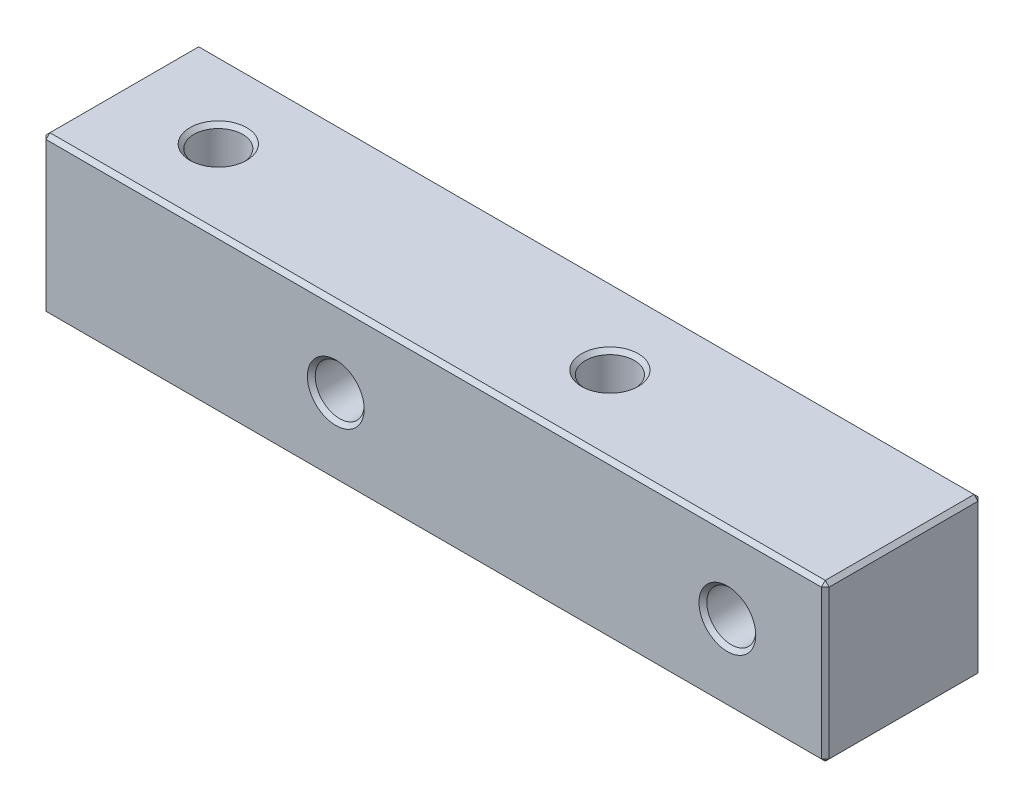
SolidWorks part; units mm, degrees
ref_plane "前视基准面" through (0, 0, 0) normal (0, 0, 1) x (1, 0, 0)
ref_plane "上视基准面" through (0, 0, 0) normal (0, 1, 0) x (1, 0, 0)
ref_plane "右视基准面" through (0, 0, 0) normal (1, 0, 0) x (0, 0, -1)
sketch "草图1" plane through (0, 0, 0) normal (0, 1, 0) x (1, 0, 0)
  line L1 (-20, 4) -> (20, 4)
  line L2 (-20, 4) -> (-20, -4)
  line L3 (-20, -4) -> (20, -4)
  line L4 (20, 4) -> (20, -4)
  line L5 (-20, 4) -> (20, -4) construction
  line L6 (-20, -4) -> (20, 4) construction
  point P0 (0, 0)
  dimension "D1" = 8
  dimension "D2" = 40
extrude "凸台-拉伸1" add sketch "草图1" along normal mid plane 8
hole_wizard "M3 螺纹孔1" positions "草图4" profile "草图6" tap size "M3" standard "GB" end condition through all
sketch "草图4" plane through (0, 4, 0) normal (0, 1, 0) x (1, 0, 0)
  line L0 (-20, 4) -> (-20, -4) construction
  line L1 (0, 0) -> (-50000, 0) construction
  point P0 (-15, 0)
  point P2 (5, 0)
  dimension "D1" = 5
  dimension "D2" = 20
sketch "草图6" plane through (-15, 4, 0) normal (1, 0, 0) x (0, 0, 1)
  line L0 (0, 0) -> (0, 8)
  line L1 (0, 8) -> (1.25, 8)
  line L2 (1.25, 8) -> (1.25, 0)
  line L5 (1.25, 0) -> (0, 0)
  line L11 (0, -6.35) -> (0, 107.95) construction
  dimension "通孔螺纹孔钻头直径" = 2.5
  dimension "通孔螺纹孔钻头深度" = 8
cosmetic thread "孔螺蚊线1"
cosmetic thread "孔螺蚊线2"
hole_wizard "M3 螺纹孔2" positions "草图7" profile "草图8" tap size "M3" standard "GB" end condition through all
sketch "草图7" plane through (0, 0, -4) normal (0, 0, -1) x (-1, 0, 0)
  line L0 (0, 0) -> (-50000, 0) construction
  line L1 (-20, 4) -> (-20, -4) construction
  point P0 (-15, 0)
  point P2 (5, 0)
  dimension "D1" = 5
  dimension "D2" = 20
sketch "草图8" plane through (15, 0, -4) normal (1, 0, 0) x (0, 1, 0)
  line L0 (0, 0) -> (0, 8)
  line L1 (0, 8) -> (1.25, 8)
  line L2 (1.25, 8) -> (1.25, 0)
  line L5 (1.25, 0) -> (0, 0)
  line L11 (0, -6.35) -> (0, 107.95) construction
  dimension "通孔螺纹孔钻头直径" = 2.5
  dimension "通孔螺纹孔钻头深度" = 8
cosmetic thread "孔螺蚊线3"
cosmetic thread "孔螺蚊线4"
chamfer "倒角1" distance 0.2 angle 45 20 edges at (5, -4, 1.25) (-15, -4, 1.25) (-6.25, 0, 4) (13.75, 0, 4) (5, 4, 1.25) (-15, 4, 1.25) (-20, -4, 0) (20, -4, 0) (-20, 0, 4) (0, -4, 4) (20, 0, 4) (0, 4, 4) (-20, 4, 0) (20, 4, 0) (20, 0, -4) (0, 4, -4) (-20, 0, -4) (0, -4, -4) (-6.25, 0, -4) (13.75, 0, -4)
